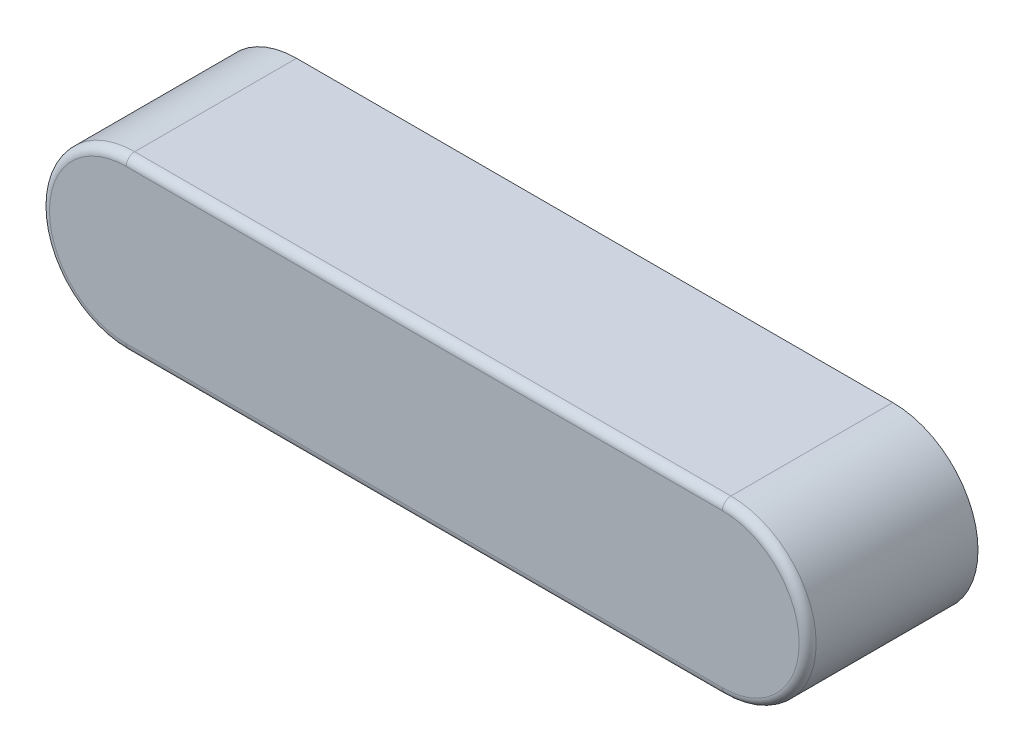
SolidWorks part; units mm, degrees
ref_plane "前视基准面" through (0, 0, 0) normal (0, 0, 1) x (1, 0, 0)
ref_plane "上视基准面" through (0, 0, 0) normal (0, 1, 0) x (1, 0, 0)
ref_plane "右视基准面" through (0, 0, 0) normal (1, 0, 0) x (0, 0, -1)
other "Configuration Table"
sketch "草图1" plane through (0, 0, 0) normal (0, 0, 1) x (1, 0, 0)
  line L1 (-4.8176, 2.2906) -> (2.1824, 2.2906)
  line L3 (-4.8176, 0.2906) -> (2.1824, 0.2906)
  arc A0 (-4.8176, 2.2906) -> (-4.8176, 0.2906) centre (-4.8176, 1.2906) ccw
  arc A1 (2.1824, 0.2906) -> (2.1824, 2.2906) centre (2.1824, 1.2906) ccw
  dimension "D1" = 7
  dimension "D2" = 2
extrude "凸台-拉伸1" add sketch "草图1" along normal blind 2
fillet "圆角1" radius 0.1 4 edges at (-1.3176, 2.2906, 2) (3.1824, 1.2906, 2) (-1.3176, 0.2906, 2) (-5.8176, 1.2906, 2)
